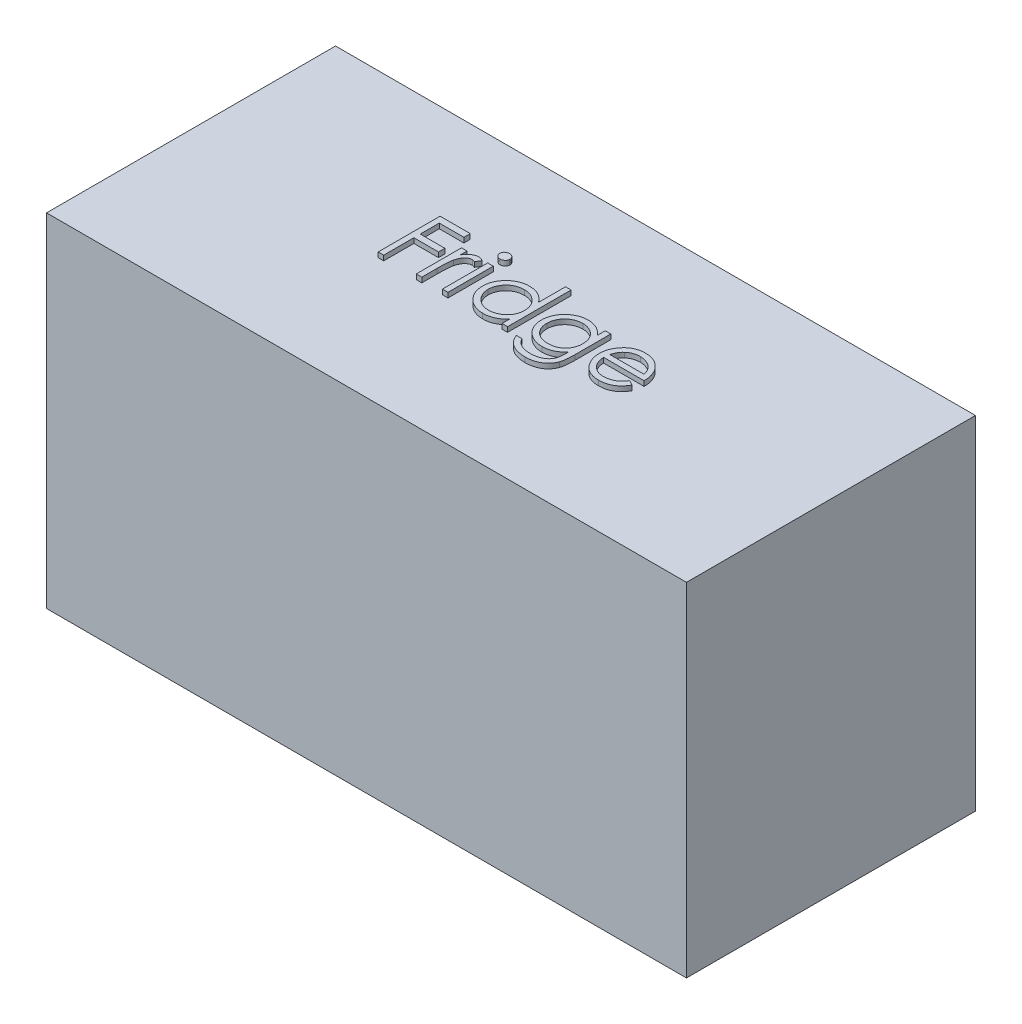
SolidWorks part; units mm, degrees
ref_plane "Front Plane" through (0, 0, 0) normal (0, 0, 1) x (1, 0, 0)
ref_plane "Top Plane" through (0, 0, 0) normal (0, 1, 0) x (1, 0, 0)
ref_plane "Right Plane" through (0, 0, 0) normal (1, 0, 0) x (0, 0, -1)
sketch "Sketch1" plane through (0, 0, 0) normal (0, 1, 0) x (1, 0, 0)
  line L1 (-775, -350) -> (775, -350)
  line L2 (-775, -350) -> (-775, 350)
  line L3 (-775, 350) -> (775, 350)
  line L4 (775, -350) -> (775, 350)
  line L5 (-775, -350) -> (775, 350) construction
  line L6 (-775, 350) -> (775, -350) construction
  point P0 (0, 0)
  dimension "D1" = 1550
  dimension "D2" = 700
extrude "Boss-Extrude1" add sketch "Sketch1" along normal blind 830
sketch "Sketch2" plane through (0, 830, 0) normal (0, 1, 0) x (1, 0, 0)
  text T0 "Fridge" font "Century Gothic" height 150
extrude "Boss-Extrude2" add sketch "Sketch2" along normal blind 12
